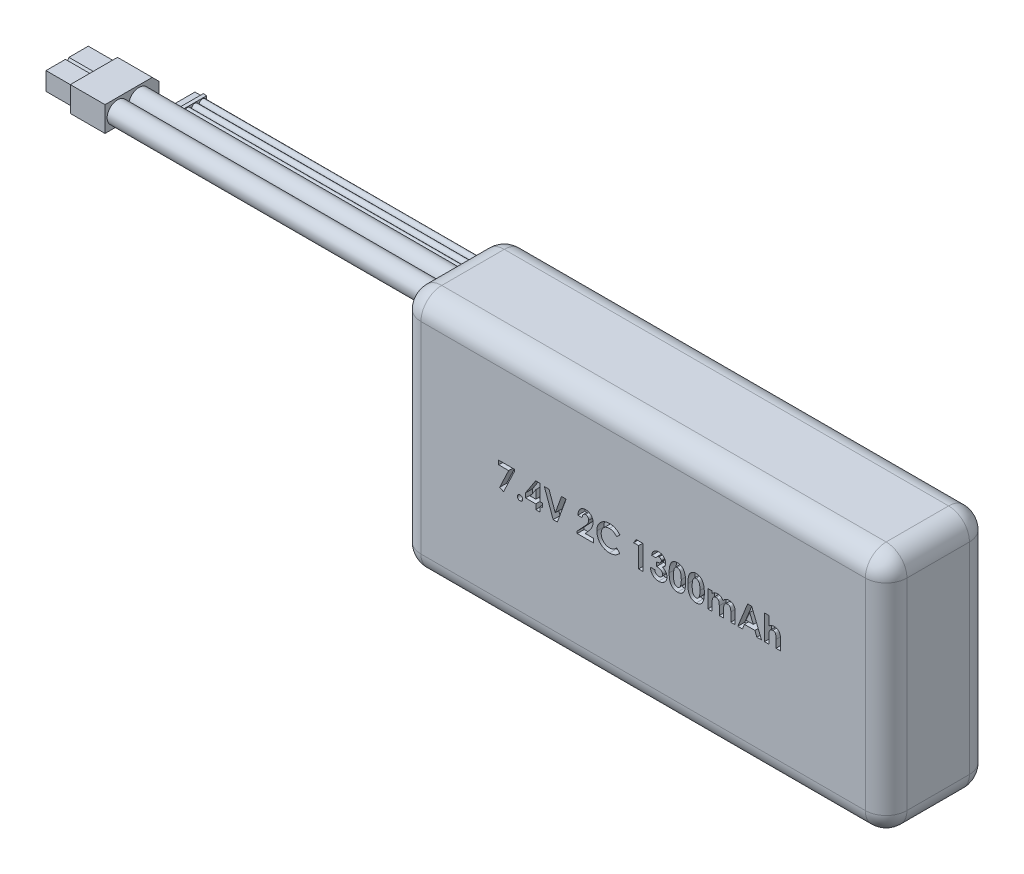
SolidWorks part; units mm, degrees
ref_plane "正面" through (0, 0, 0) normal (0, 0, 1) x (1, 0, 0)
ref_plane "平面" through (0, 0, 0) normal (0, 1, 0) x (1, 0, 0)
ref_plane "右側面" through (0, 0, 0) normal (1, 0, 0) x (0, 0, -1)
sketch "ｽｹｯﾁ1" plane through (0, 0, 0) normal (0, 0, 1) x (1, 0, 0)
  line L1 (35, -17.5) -> (-35, -17.5)
  line L2 (35, -17.5) -> (35, 17.5)
  line L3 (35, 17.5) -> (-35, 17.5)
  line L4 (-35, -17.5) -> (-35, 17.5)
  line L5 (35, -17.5) -> (-35, 17.5) construction
  line L6 (35, 17.5) -> (-35, -17.5) construction
  point P0 (0, 0)
  dimension "D1" = 70
  dimension "D2" = 35
extrude "ﾎﾞｽ - 押し出し1" add sketch "ｽｹｯﾁ1" along normal blind 15
fillet "ﾌｨﾚｯﾄ2" radius 3 12 edges at (0, 17.5, 15) (0, 17.5, 0) (35, 0, 15) (35, 17.5, 7.5) (35, 0, 0) (0, -17.5, 15) (35, -17.5, 7.5) (0, -17.5, 0) (-35, 17.5, 7.5) (-35, 0, 15) (-35, -17.5, 7.5) (-35, 0, 0)
sketch "ｽｹｯﾁ2" plane through (0, 0, 15) normal (0, 0, 1) x (1, 0, 0)
  text T0 "<b>7.4V 2C 1300mAh</b>"
extrude "ｶｯﾄ - 押し出し2" cut sketch "ｽｹｯﾁ2" against normal blind 1
sketch "ｽｹｯﾁ3" plane through (-35, 0, 0) normal (-1, 0, 0) x (0, 0, 1)
  line L0 (12, 14.5) -> (3, 14.5) construction
  line L1 (12, -14.5) -> (12, 14.5) construction
  circle A0 centre (10.7, 14.5) radius 1.5
  circle A1 centre (7.6, 14.5) radius 1.5
  dimension "D1" = 3
  dimension "D2" = 1.3
  dimension "D3" = 3.1
extrude "ﾎﾞｽ - 押し出し2" add sketch "ｽｹｯﾁ3" along normal blind 50 and the other way blind 5
sketch "ｽｹｯﾁ5" plane through (-85, 0, 0) normal (-1, 0, 0) x (0, 0, 1)
  line L1 (12.5, 16.3) -> (4.7, 16.3)
  line L2 (12.5, 16.3) -> (12.5, 12.7)
  line L3 (12.5, 12.7) -> (4.7, 12.7)
  line L4 (4.7, 16.3) -> (4.7, 12.7)
  arc A0 (12, 15.2483) -> (9.2, 14.5) centre (10.7, 14.5) ccw construction
  circle A1 centre (10.7, 14.5) radius 1.5 construction
  dimension "D1" = 1.8
  dimension "D2" = 3.6
  dimension "D3" = 1.8
  dimension "D4" = 7.8
extrude "ﾎﾞｽ - 押し出し3" add sketch "ｽｹｯﾁ5" against normal blind 5
chamfer "面取り1" distance 1 angle 45 2 edges at (-82.5, 12.7, 4.7) (-82.5, 16.3, 4.7)
sketch3d "3Dｽｹｯﾁ1"
  line L0 (-85, 13.2, 12) -> (-85, 15.8, 12)
  line L1 (-85, 15.8, 12) -> (-85, 15.8, 5.9071)
  line L2 (-85, 15.8, 5.9071) -> (-85, 15.0929, 5.2)
  line L3 (-85, 15.0929, 5.2) -> (-85, 13.9071, 5.2)
  line L4 (-85, 13.9071, 5.2) -> (-85, 13.2, 5.9071)
  line L5 (-85, 13.2, 5.9071) -> (-85, 13.2, 12)
  line L6 (-85, 13.2, 12) -> (-85, 15.8, 12)
  line L7 (-85, 15.8, 12) -> (-85, 15.8, 5.9071)
  line L8 (-85, 15.8, 5.9071) -> (-85, 15.0929, 5.2)
  line L9 (-85, 15.0929, 5.2) -> (-85, 13.9071, 5.2)
  line L10 (-85, 13.9071, 5.2) -> (-85, 13.2, 5.9071)
  line L11 (-85, 13.2, 5.9071) -> (-85, 13.2, 12)
  dimension "D1" = 0.5
extrude "ﾎﾞｽ - 押し出し4" add sketch "3Dｽｹｯﾁ1" along direction (1, 0, 0) on the side against the normal blind 4 contours L6 L7 L8 L9 L10 L11
sketch "ｽｹｯﾁ6" plane through (-89, 0, 0) normal (-1, 0, 0) x (0, 0, 1)
  line L0 (8.7, 15.8) -> (8.95, 15.367)
  line L1 (12, 15.8) -> (5.9071, 15.8) construction
  line L2 (8.95, 15.367) -> (9.2, 15.8)
  line L3 (12, 15.8) -> (5.9071, 15.8) construction
  line L4 (9.2, 15.8) -> (8.7, 15.8)
  line L5 (8.7, 13.2) -> (8.95, 13.633)
  line L6 (5.9071, 13.2) -> (12, 13.2) construction
  line L7 (8.95, 13.633) -> (9.2, 13.2)
  line L8 (9.2, 13.2) -> (8.7, 13.2)
  line L9 (12, 13.2) -> (12, 15.8) construction
  dimension "D1" = 2.8
  dimension "D2" = 0.5
extrude "ｶｯﾄ - 押し出し3" cut sketch "ｽｹｯﾁ6" against normal up to surface (4 mm away)
sketch "ｽｹｯﾁ7" plane through (-35, 0, 0) normal (-1, 0, 0) x (0, 0, 1)
  line L0 (6.1, 14.5) -> (3, 14.5) construction
  circle A0 centre (5.65, 14.5) radius 0.5
  circle A1 centre (4.55, 14.5) radius 0.5
  circle A2 centre (3.45, 14.5) radius 0.5
  dimension "D1" = 1
  dimension "D2" = 1.1
  dimension "D3" = 1.1
extrude "ﾎﾞｽ - 押し出し5" add sketch "ｽｹｯﾁ7" along normal blind 40 and the other way blind 4
sketch "ｽｹｯﾁ8" plane through (-75, 0, 0) normal (-1, 0, 0) x (0, 0, 1)
  line L1 (6.25, 15.1) -> (2.85, 15.1)
  line L2 (6.25, 15.1) -> (6.25, 13.9)
  line L3 (6.25, 13.9) -> (2.85, 13.9)
  line L4 (2.85, 15.1) -> (2.85, 13.9)
  circle A0 centre (3.45, 14.5) radius 0.5 construction
  arc A1 (6.1122, 14.6908) -> (6.1122, 14.3092) centre (5.65, 14.5) ccw construction
  dimension "D1" = 0.6
  dimension "D2" = 1.2
  dimension "D3" = 0.6
  dimension "D4" = 0.6
extrude "ﾎﾞｽ - 押し出し6" add sketch "ｽｹｯﾁ8" along normal blind 0.5
sketch3d "3Dｽｹｯﾁ2"
  line L0 (-75.5, 14.9, 3.05) -> (-75.5, 14.1, 3.05)
  line L1 (-75.5, 14.1, 3.05) -> (-75.5, 14.1, 5.9477)
  line L2 (-75.5, 14.9, 5.9477) -> (-75.5, 14.9, 3.05)
  line L3 (-75.5, 14.9, 3.05) -> (-75.5, 14.1, 3.05)
  line L4 (-75.5, 14.1, 3.05) -> (-75.5, 14.1, 5.9477)
  line L5 (-75.5, 14.9, 5.9477) -> (-75.5, 14.9, 3.05)
  arc A0 (-75.5, 14.9, 5.9477) -> (-75.5, 14.1, 5.9477) centre (-75.5, 14.5, 7.6) ccw
  arc A1 (-75.5, 14.9, 5.9477) -> (-75.5, 14.1, 5.9477) centre (-75.5, 14.5, 7.6) ccw
  point P5 (-77.2, 14.5, 7.6)
  point P6 (-77.2, 14.5, 7.6)
  dimension "D1" = 0.2
extrude "ﾎﾞｽ - 押し出し7" add sketch "3Dｽｹｯﾁ2" along direction (1, 0, 0) on the side against the normal blind 1
